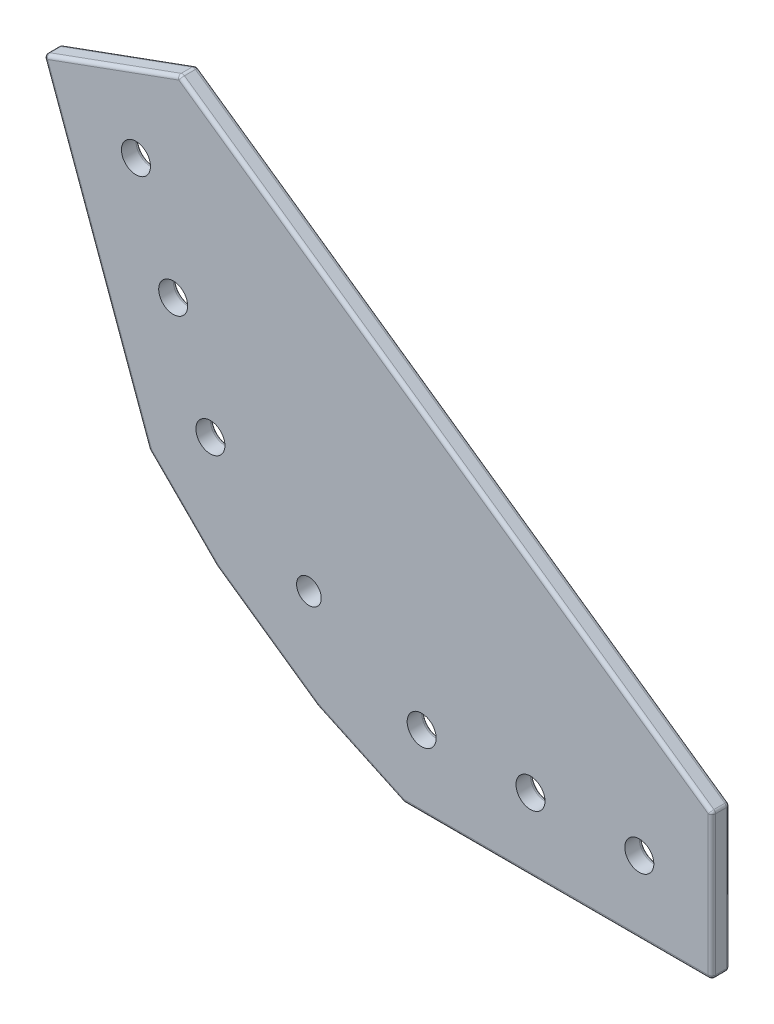
SolidWorks part; units mm, degrees
ref_plane "Front Plane" through (0, 0, 0) normal (0, 0, 1) x (1, 0, 0)
ref_plane "Top Plane" through (0, 0, 0) normal (0, 1, 0) x (1, 0, 0)
ref_plane "Right Plane" through (0, 0, 0) normal (1, 0, 0) x (0, 0, -1)
sketch "Sketch1" plane through (0, 0, 0) normal (0, 0, 1) x (1, 0, 0)
  line L0 (83.2382, -33.8685) -> (83.2382, -73.8685)
  line L1 (-1.7618, -73.8685) -> (-25.6213, -62.7427)
  line L2 (-25.6213, -62.7427) -> (-53.4724, -43.2411)
  line L3 (-53.4724, -43.2411) -> (-72.0877, -24.6258)
  line L4 (-63.5717, 68.9289) -> (-101.1594, 55.2481)
  line L5 (83.2382, -33.8685) -> (-63.5717, 68.9289)
  line L6 (-101.1594, 55.2481) -> (-72.0877, -24.6258)
  line L7 (-1.7618, -73.8685) -> (83.2382, -73.8685)
  line L8 (-25.6213, -62.7427) -> (23.7588, 7.7794)
  line L9 (-53.4724, -43.2411) -> (-4.0924, 27.281)
  dimension "D1" = 40
  dimension "D2" = 40
  dimension "D3" = 85
  dimension "D4" = 85
  dimension "D5" = 110
  dimension "D6" = 20
  dimension "D7" = 125
  dimension "D8" = 80
  dimension "D9" = 80
  dimension "D10" = 34
  dimension "D11" = 86.0915
  dimension "D12" = 90
  dimension "D13" = 15
extrude "Boss-Extrude1" add sketch "Sketch1" along normal blind 5 contours L3 L9 L5 L4 L6 | L9 L2 L8 L5 | L8 L1 L7 L0 L5
sketch "Sketch2" plane through (0, 0, 0) normal (0, 0, -1) x (-1, 0, 0)
  line L0 (-83.2382, -33.8685) -> (62.7801, -33.9334) construction
  line L1 (53.4724, -43.2411) -> (72.0877, -24.6258) construction
  line L2 (63.5717, 68.9289) -> (13.6915, -68.3056) construction
  line L3 (1.7618, -73.8685) -> (25.6213, -62.7427) construction
  line L4 (-83.2382, -53.8685) -> (38.2949, -53.8685) construction
  line L5 (-83.2382, -33.8685) -> (-83.2382, -73.8685) construction
  line L6 (25.6213, -62.7427) -> (53.4724, -43.2411) construction
  line L7 (82.3656, 62.0885) -> (40.7988, -52.1152) construction
  line L8 (63.5717, 68.9289) -> (101.1594, 55.2481) construction
  line L9 (-53.2382, -53.8685) -> (68.2949, -53.8685) construction
  line L10 (-23.2382, -53.8685) -> (98.2949, -53.8685) construction
  line L14 (101.1594, 55.2481) -> (72.0877, -24.6258) construction
  circle A0 centre (-63.2382, -53.8685) radius 4
  circle A2 centre (-33.2382, -53.8685) radius 4
  circle A3 centre (-3.2382, -53.8685) radius 4
  circle A4 centre (75.5252, 43.2946) radius 4
  circle A5 centre (65.2646, 15.1039) radius 4
  circle A6 centre (55.004, -13.0869) radius 4
  dimension "D1" = 8
  dimension "D2" = 3
  dimension "D3" = 20
  dimension "D4" = 8
  dimension "D5" = 20
  dimension "D7" = 30
  dimension "D8" = 30
  dimension "D6" = 3
extrude "Cut-Extrude1" cut sketch "Sketch2" against normal through all contours A4 | A3 | A2 | A0 | A5 | A6
fillet "Fillet1" radius 1 14 edges at (-79.5252, 43.2946, 0) (-69.2646, 15.1039, 0) (59.2382, -53.8685, 0) (29.2382, -53.8685, 0) (-59.004, -13.0869, 0) (-0.7618, -53.8685, 0) (83.2382, -33.8685, 2.5) (-63.5717, 68.9289, 2.5) (-101.1594, 55.2481, 2.5) (-53.4724, -43.2411, 2.5) (-72.0877, -24.6258, 2.5) (-25.6213, -62.7427, 2.5) (-1.7618, -73.8685, 2.5) (83.2382, -73.8685, 2.5)
fillet "Fillet2" radius 1 32 edges at (-1.7566, -73.8448, 5) (-1.7566, -73.8448, 0) (-13.7524, -68.2772, 5) (-13.7524, -68.2772, 0) (-25.6194, -62.7394, 5) (-25.6194, -62.7394, 0) (-39.5469, -52.9919, 5) (-39.5469, -52.9919, 0) (-53.47, -43.2381, 5) (-53.47, -43.2381, 0) (-62.7326, -33.9809, 0) (-62.7326, -33.9809, 5) (-72.0672, -24.6127, 5) (-72.0672, -24.6127, 0) (-86.4905, 14.9455, 5) (-86.4905, 14.9455, 0) (-100.784, 55.073, 5) (-100.784, 55.073, 0) (-82.1403, 62.1705, 5) (-82.1403, 62.1705, 0) (-63.5883, 68.8026, 5) (-63.5883, 68.8026, 0) (9.8332, 17.5302, 5) (9.8332, 17.5302, 0) (83.1252, -33.9273, 5) (83.1252, -33.9273, 0) (83.2382, -53.6288, 0) (83.2382, -53.6288, 5) (82.9453, -73.5756, 5) (82.9453, -73.5756, 0) (40.349, -73.8685, 5) (40.349, -73.8685, 0)
sketch "Sketch3" plane through (0, 0, 5) normal (0, 0, 1) x (1, 0, 0)
  line L0 (-22.8557, -20.8513) -> (-27.3291, -17.719)
  line L1 (-22.8557, -20.8513) -> (-27.3291, -17.719)
  line L2 (-28.5166, -18.4755) -> (-27.1491, -26.2307)
  line L3 (-28.5166, -18.4755) -> (-27.1491, -26.2307)
  line L4 (-25.9166, -28.1654) -> (-20.8794, -31.6925)
  line L5 (-25.9166, -28.1654) -> (-20.8794, -31.6925)
  line L6 (-18.6398, -32.189) -> (-10.8846, -30.8215)
  line L7 (-18.6398, -32.189) -> (-10.8846, -30.8215)
  line L8 (-10.5799, -29.4469) -> (-15.0533, -26.3146)
  line L9 (-10.5799, -29.4469) -> (-15.0533, -26.3146)
  line L10 (-15.2404, -25.2533) -> (-13.5359, -22.819)
  line L11 (-15.2404, -25.2533) -> (-13.5359, -22.819)
  line L12 (-12.4746, -22.6319) -> (-2.4896, -29.6235)
  line L13 (-12.4746, -22.6319) -> (-2.4896, -29.6235)
  line L14 (-1.741, -33.8685) -> (-8.7326, -43.8536)
  line L15 (-1.741, -33.8685) -> (-8.7326, -43.8536)
  line L16 (-9.7939, -44.0407) -> (-12.2283, -42.3361)
  line L17 (-9.7939, -44.0407) -> (-12.2283, -42.3361)
  line L18 (-12.4154, -41.2749) -> (-9.2831, -36.8015)
  line L19 (-12.4154, -41.2749) -> (-9.2831, -36.8015)
  line L20 (-10.0396, -35.614) -> (-17.7948, -36.9814)
  line L21 (-10.0396, -35.614) -> (-17.7948, -36.9814)
  line L22 (-19.7295, -38.214) -> (-23.2566, -43.2512)
  line L23 (-19.7295, -38.214) -> (-23.2566, -43.2512)
  line L24 (-23.7531, -45.4908) -> (-22.3856, -53.2459)
  line L25 (-23.7531, -45.4908) -> (-22.3856, -53.2459)
  line L26 (-21.011, -53.5507) -> (-17.8787, -49.0773)
  line L27 (-21.011, -53.5507) -> (-17.8787, -49.0773)
  line L28 (-16.8174, -48.8902) -> (-14.3831, -50.5947)
  line L29 (-16.8174, -48.8902) -> (-14.3831, -50.5947)
  line L30 (-14.196, -51.656) -> (-21.1876, -61.641)
  line L31 (-14.196, -51.656) -> (-21.1876, -61.641)
  line L32 (-25.4326, -62.3895) -> (-35.4177, -55.3979)
  line L33 (-25.4326, -62.3895) -> (-35.4177, -55.3979)
  line L34 (-35.6048, -54.3367) -> (-33.9002, -51.9023)
  line L35 (-35.6048, -54.3367) -> (-33.9002, -51.9023)
  line L36 (-32.839, -51.7152) -> (-28.3656, -54.8475)
  line L37 (-32.839, -51.7152) -> (-28.3656, -54.8475)
  line L38 (-27.1781, -54.091) -> (-28.5455, -46.3358)
  line L39 (-27.1781, -54.091) -> (-28.5455, -46.3358)
  line L40 (-29.7781, -44.4011) -> (-34.8153, -40.874)
  line L41 (-29.7781, -44.4011) -> (-34.8153, -40.874)
  line L42 (-37.0549, -40.3775) -> (-44.81, -41.745)
  line L43 (-37.0549, -40.3775) -> (-44.81, -41.745)
  line L44 (-45.1148, -43.1196) -> (-40.6414, -46.2519)
  line L45 (-45.1148, -43.1196) -> (-40.6414, -46.2519)
  line L46 (-40.4543, -47.3131) -> (-42.1588, -49.7475)
  line L47 (-40.4543, -47.3131) -> (-42.1588, -49.7475)
  line L48 (-43.2201, -49.9346) -> (-53.2051, -42.943)
  line L49 (-43.2201, -49.9346) -> (-53.2051, -42.943)
  line L50 (-53.9537, -38.698) -> (-46.962, -28.7129)
  line L51 (-53.9537, -38.698) -> (-46.962, -28.7129)
  line L52 (-45.9008, -28.5258) -> (-43.4664, -30.2303)
  line L53 (-45.9008, -28.5258) -> (-43.4664, -30.2303)
  line L54 (-43.2793, -31.2916) -> (-46.4116, -35.765)
  line L55 (-43.2793, -31.2916) -> (-46.4116, -35.765)
  line L56 (-45.6551, -36.9525) -> (-37.8999, -35.585)
  line L57 (-45.6551, -36.9525) -> (-37.8999, -35.585)
  line L58 (-35.9652, -34.3525) -> (-32.4381, -29.3153)
  line L59 (-35.9652, -34.3525) -> (-32.4381, -29.3153)
  line L60 (-31.9416, -27.0757) -> (-33.3091, -19.3205)
  line L61 (-31.9416, -27.0757) -> (-33.3091, -19.3205)
  line L62 (-34.6837, -19.0158) -> (-37.816, -23.4892)
  line L63 (-34.6837, -19.0158) -> (-37.816, -23.4892)
  line L64 (-38.8772, -23.6763) -> (-41.3116, -21.9718)
  line L65 (-38.8772, -23.6763) -> (-41.3116, -21.9718)
  line L66 (-41.4987, -20.9105) -> (-34.5071, -10.9254)
  line L67 (-41.4987, -20.9105) -> (-34.5071, -10.9254)
  line L68 (-30.2621, -10.1769) -> (-20.277, -17.1685)
  line L69 (-30.2621, -10.1769) -> (-20.277, -17.1685)
  line L70 (-20.0899, -18.2298) -> (-21.7945, -20.6642)
  line L71 (-20.0899, -18.2298) -> (-21.7945, -20.6642)
  line L72 (-34.2017, -31.8339) -> (-21.493, -40.7326) construction
  line L73 (-32.2967, -42.6376) -> (-23.398, -29.9289) construction
  arc A0 (-27.3291, -17.719) -> (-28.5166, -18.4755) centre (-27.7662, -18.3432) ccw
  arc A1 (-27.3291, -17.719) -> (-28.5166, -18.4755) centre (-27.7662, -18.3432) ccw
  arc A2 (-27.1491, -26.2307) -> (-25.9166, -28.1654) centre (-24.1975, -25.7102) ccw
  arc A3 (-27.1491, -26.2307) -> (-25.9166, -28.1654) centre (-24.1975, -25.7102) ccw
  arc A4 (-20.8794, -31.6925) -> (-18.6398, -32.189) centre (-19.1603, -29.2373) ccw
  arc A5 (-20.8794, -31.6925) -> (-18.6398, -32.189) centre (-19.1603, -29.2373) ccw
  arc A6 (-10.8846, -30.8215) -> (-10.5799, -29.4469) centre (-11.017, -30.0711) ccw
  arc A7 (-10.8846, -30.8215) -> (-10.5799, -29.4469) centre (-11.017, -30.0711) ccw
  arc A8 (-15.2404, -25.2533) -> (-15.0533, -26.3146) centre (-14.6162, -25.6904) ccw
  arc A9 (-15.2404, -25.2533) -> (-15.0533, -26.3146) centre (-14.6162, -25.6904) ccw
  arc A10 (-12.4746, -22.6319) -> (-13.5359, -22.819) centre (-12.9117, -23.256) ccw
  arc A11 (-12.4746, -22.6319) -> (-13.5359, -22.819) centre (-12.9117, -23.256) ccw
  arc A12 (-1.741, -33.8685) -> (-2.4896, -29.6235) centre (-4.2378, -32.1202) ccw
  arc A13 (-1.741, -33.8685) -> (-2.4896, -29.6235) centre (-4.2378, -32.1202) ccw
  arc A14 (-9.7939, -44.0407) -> (-8.7326, -43.8536) centre (-9.3568, -43.4165) ccw
  arc A15 (-9.7939, -44.0407) -> (-8.7326, -43.8536) centre (-9.3568, -43.4165) ccw
  arc A16 (-12.4154, -41.2749) -> (-12.2283, -42.3361) centre (-11.7912, -41.7119) ccw
  arc A17 (-12.4154, -41.2749) -> (-12.2283, -42.3361) centre (-11.7912, -41.7119) ccw
  arc A18 (-9.2831, -36.8015) -> (-10.0396, -35.614) centre (-9.9073, -36.3644) ccw
  arc A19 (-9.2831, -36.8015) -> (-10.0396, -35.614) centre (-9.9073, -36.3644) ccw
  arc A20 (-17.7948, -36.9814) -> (-19.7295, -38.214) centre (-17.2743, -39.9331) ccw
  arc A21 (-17.7948, -36.9814) -> (-19.7295, -38.214) centre (-17.2743, -39.9331) ccw
  arc A22 (-23.2566, -43.2512) -> (-23.7531, -45.4908) centre (-20.8014, -44.9703) ccw
  arc A23 (-23.2566, -43.2512) -> (-23.7531, -45.4908) centre (-20.8014, -44.9703) ccw
  arc A24 (-22.3856, -53.2459) -> (-21.011, -53.5507) centre (-21.6352, -53.1136) ccw
  arc A25 (-22.3856, -53.2459) -> (-21.011, -53.5507) centre (-21.6352, -53.1136) ccw
  arc A26 (-16.8174, -48.8902) -> (-17.8787, -49.0773) centre (-17.2545, -49.5144) ccw
  arc A27 (-16.8174, -48.8902) -> (-17.8787, -49.0773) centre (-17.2545, -49.5144) ccw
  arc A28 (-14.196, -51.656) -> (-14.3831, -50.5947) centre (-14.8202, -51.2189) ccw
  arc A29 (-14.196, -51.656) -> (-14.3831, -50.5947) centre (-14.8202, -51.2189) ccw
  arc A30 (-25.4326, -62.3895) -> (-21.1876, -61.641) centre (-23.6843, -59.8928) ccw
  arc A31 (-25.4326, -62.3895) -> (-21.1876, -61.641) centre (-23.6843, -59.8928) ccw
  arc A32 (-35.6048, -54.3367) -> (-35.4177, -55.3979) centre (-34.9806, -54.7737) ccw
  arc A33 (-35.6048, -54.3367) -> (-35.4177, -55.3979) centre (-34.9806, -54.7737) ccw
  arc A34 (-32.839, -51.7152) -> (-33.9002, -51.9023) centre (-33.276, -52.3394) ccw
  arc A35 (-32.839, -51.7152) -> (-33.9002, -51.9023) centre (-33.276, -52.3394) ccw
  arc A36 (-28.3656, -54.8475) -> (-27.1781, -54.091) centre (-27.9285, -54.2233) ccw
  arc A37 (-28.3656, -54.8475) -> (-27.1781, -54.091) centre (-27.9285, -54.2233) ccw
  arc A38 (-28.5455, -46.3358) -> (-29.7781, -44.4011) centre (-31.4972, -46.8563) ccw
  arc A39 (-28.5455, -46.3358) -> (-29.7781, -44.4011) centre (-31.4972, -46.8563) ccw
  arc A40 (-34.8153, -40.874) -> (-37.0549, -40.3775) centre (-36.5344, -43.3292) ccw
  arc A41 (-34.8153, -40.874) -> (-37.0549, -40.3775) centre (-36.5344, -43.3292) ccw
  arc A42 (-44.81, -41.745) -> (-45.1148, -43.1196) centre (-44.6777, -42.4954) ccw
  arc A43 (-44.81, -41.745) -> (-45.1148, -43.1196) centre (-44.6777, -42.4954) ccw
  arc A44 (-40.4543, -47.3131) -> (-40.6414, -46.2519) centre (-41.0785, -46.8761) ccw
  arc A45 (-40.4543, -47.3131) -> (-40.6414, -46.2519) centre (-41.0785, -46.8761) ccw
  arc A46 (-43.2201, -49.9346) -> (-42.1588, -49.7475) centre (-42.783, -49.3104) ccw
  arc A47 (-43.2201, -49.9346) -> (-42.1588, -49.7475) centre (-42.783, -49.3104) ccw
  arc A48 (-53.9537, -38.698) -> (-53.2051, -42.943) centre (-51.4569, -40.4462) ccw
  arc A49 (-53.9537, -38.698) -> (-53.2051, -42.943) centre (-51.4569, -40.4462) ccw
  arc A50 (-45.9008, -28.5258) -> (-46.962, -28.7129) centre (-46.3379, -29.15) ccw
  arc A51 (-45.9008, -28.5258) -> (-46.962, -28.7129) centre (-46.3379, -29.15) ccw
  arc A52 (-43.2793, -31.2916) -> (-43.4664, -30.2303) centre (-43.9035, -30.8545) ccw
  arc A53 (-43.2793, -31.2916) -> (-43.4664, -30.2303) centre (-43.9035, -30.8545) ccw
  arc A54 (-46.4116, -35.765) -> (-45.6551, -36.9525) centre (-45.7874, -36.2021) ccw
  arc A55 (-46.4116, -35.765) -> (-45.6551, -36.9525) centre (-45.7874, -36.2021) ccw
  arc A56 (-37.8999, -35.585) -> (-35.9652, -34.3525) centre (-38.4204, -32.6334) ccw
  arc A57 (-37.8999, -35.585) -> (-35.9652, -34.3525) centre (-38.4204, -32.6334) ccw
  arc A58 (-32.4381, -29.3153) -> (-31.9416, -27.0757) centre (-34.8933, -27.5962) ccw
  arc A59 (-32.4381, -29.3153) -> (-31.9416, -27.0757) centre (-34.8933, -27.5962) ccw
  arc A60 (-33.3091, -19.3205) -> (-34.6837, -19.0158) centre (-34.0595, -19.4529) ccw
  arc A61 (-33.3091, -19.3205) -> (-34.6837, -19.0158) centre (-34.0595, -19.4529) ccw
  arc A62 (-38.8772, -23.6763) -> (-37.816, -23.4892) centre (-38.4402, -23.0521) ccw
  arc A63 (-38.8772, -23.6763) -> (-37.816, -23.4892) centre (-38.4402, -23.0521) ccw
  arc A64 (-41.4987, -20.9105) -> (-41.3116, -21.9718) centre (-40.8745, -21.3476) ccw
  arc A65 (-41.4987, -20.9105) -> (-41.3116, -21.9718) centre (-40.8745, -21.3476) ccw
  arc A66 (-30.2621, -10.1769) -> (-34.5071, -10.9254) centre (-32.0103, -12.6737) ccw
  arc A67 (-30.2621, -10.1769) -> (-34.5071, -10.9254) centre (-32.0103, -12.6737) ccw
  arc A68 (-20.0899, -18.2298) -> (-20.277, -17.1685) centre (-20.7141, -17.7927) ccw
  arc A69 (-20.0899, -18.2298) -> (-20.277, -17.1685) centre (-20.7141, -17.7927) ccw
  arc A70 (-22.8557, -20.8513) -> (-21.7945, -20.6642) centre (-22.4186, -20.2271) ccw
  arc A71 (-22.8557, -20.8513) -> (-21.7945, -20.6642) centre (-22.4186, -20.2271) ccw
  circle A72 centre (-27.8473, -36.2832) radius 3.4
  dimension "D1" = 6.8
extrude "Cut-Extrude2" cut sketch "Sketch3" against normal through all contours A72
